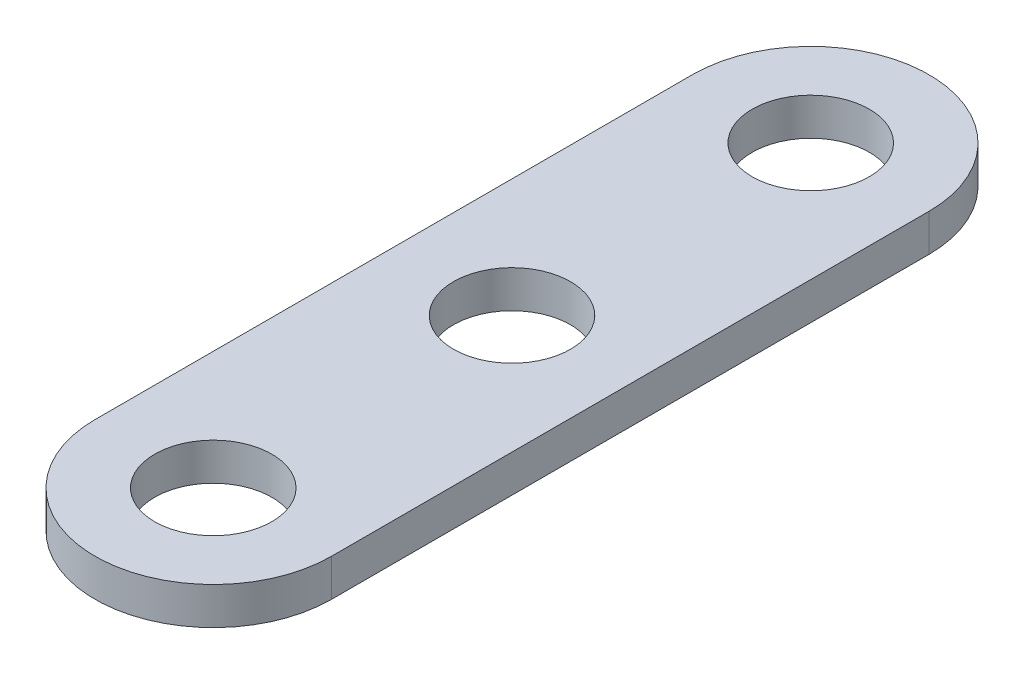
SolidWorks part; units mm, degrees
material "6061-T6 (SS)"
ref_plane "Front Plane" through (0, 0, 0) normal (0, 0, 1) x (1, 0, 0)
ref_plane "Top Plane" through (0, 0, 0) normal (0, 1, 0) x (1, 0, 0)
ref_plane "Right Plane" through (0, 0, 0) normal (1, 0, 0) x (0, 0, -1)
sketch "Sketch1" plane through (0, 0, 0) normal (0, 1, 0) x (1, 0, 0)
  line L0 (0, 12.7) -> (0, -12.7) construction
  line L1 (5.0292, -12.7) -> (5.0292, 12.7)
  line L2 (-5.0292, 12.7) -> (-5.0292, -12.7)
  circle A0 centre (0, 0) radius 2.4892
  circle A1 centre (0, 12.7) radius 2.4892
  circle A2 centre (0, -12.7) radius 2.4892
  arc A3 (-5.0292, -12.7) -> (5.0292, -12.7) centre (0, -12.7) ccw
  arc A4 (5.0292, 12.7) -> (-5.0292, 12.7) centre (0, 12.7) ccw
  point P7 (0, 0)
  dimension "D1" = 4.9784
  dimension "D2" = 4.9784
  dimension "D4" = 2.54
  dimension "D3" = 25.4
extrude "Boss-Extrude1" add sketch "Sketch1" along normal blind 1.5875
